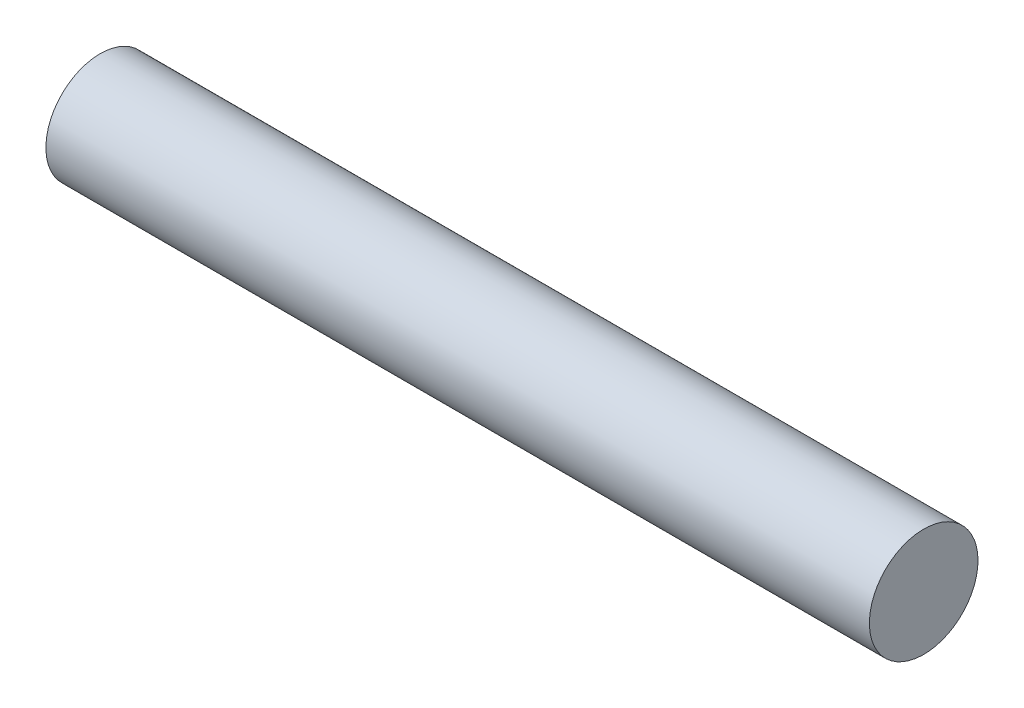
SolidWorks part; units mm, degrees
material "2024 Alaşım"
ref_plane "Ön Düzlem" through (0, 0, 0) normal (0, 0, 1) x (1, 0, 0)
ref_plane "Üst Düzlem" through (0, 0, 0) normal (0, 1, 0) x (1, 0, 0)
ref_plane "Sağ Düzlem" through (0, 0, 0) normal (1, 0, 0) x (0, 0, -1)
sketch "Çizim1" plane through (0, 0, 0) normal (1, 0, 0) x (0, 0, -1)
  circle A0 centre (0, 0) radius 6
  dimension "D1" = 12
extrude "Yükseklik-Ekstrüzyon1" add sketch "Çizim1" along normal blind 91
